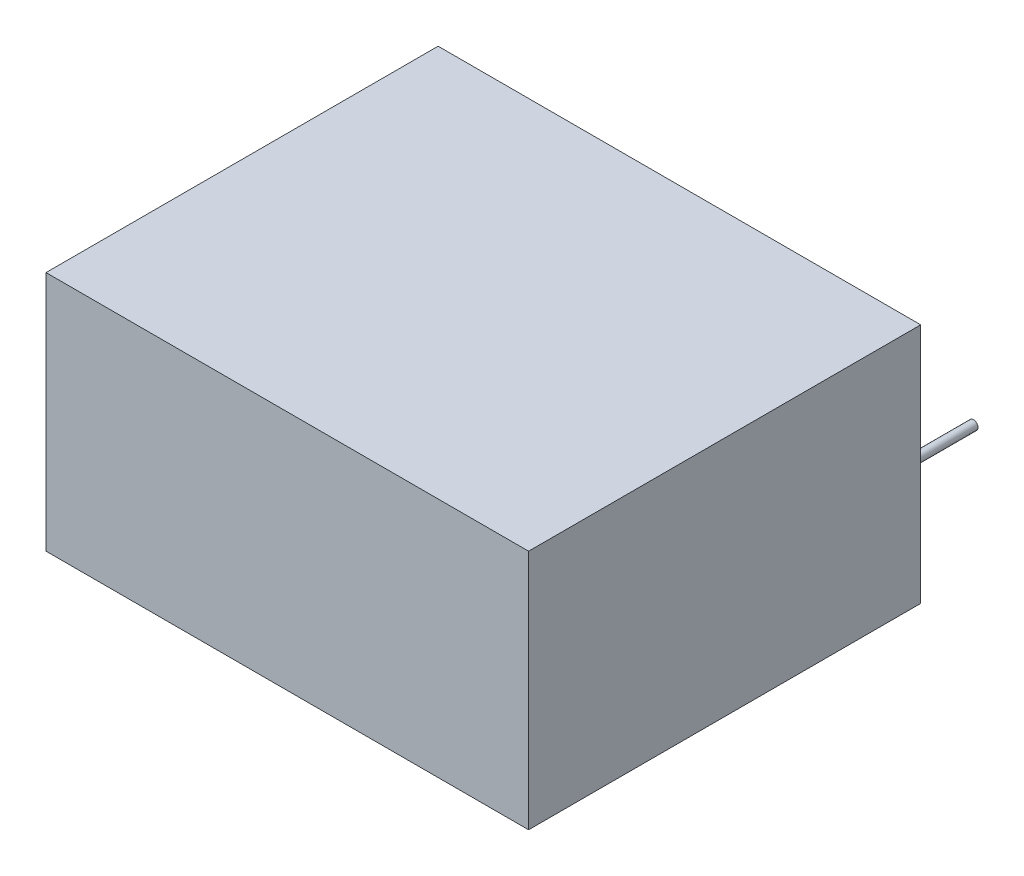
SolidWorks part; units mm, degrees
ref_plane "Front" through (0, 0, 0) normal (0, 0, 1) x (1, 0, 0)
ref_plane "Top" through (0, 0, 0) normal (0, 1, 0) x (1, 0, 0)
ref_plane "Right" through (0, 0, 0) normal (1, 0, 0) x (0, 0, -1)
sketch "Эскиз1" plane through (0, 0, 0) normal (0, 0, 1) x (1, 0, 0)
  line L1 (-0.8, -0.8) -> (0.8, -0.8)
  line L2 (-0.8, -0.8) -> (-0.8, 0.8)
  line L3 (-0.8, 0.8) -> (0.8, 0.8)
  line L4 (0.8, -0.8) -> (0.8, 0.8)
  line L5 (11.65, -0.8) -> (13.25, -0.8)
  line L6 (11.65, -0.8) -> (11.65, 0.8)
  line L7 (11.65, 0.8) -> (13.25, 0.8)
  line L8 (13.25, -0.8) -> (13.25, 0.8)
sketch "Эскиз2" plane through (0, 0, 0) normal (0, 0, 1) x (1, 0, 0)
  line L0 (-0.5, 8) -> (-0.5, -8)
  line L1 (31.5, -8) -> (31.5, 8)
  line L2 (-0.5, -8) -> (31.5, -8)
  line L3 (31.5, 8) -> (-0.5, 8)
  dimension "D1" = 32
  dimension "D2" = 16
  dimension "D3" = 8
  dimension "D4" = 0.5
extrude "Вытянуть1" add sketch "Эскиз2" along normal blind 26
sketch "Эскиз3" plane through (0, 0, 0) normal (0, 0, -1) x (-1, 0, 0)
  circle A0 centre (0, 0) radius 0.4
  circle A1 centre (-31, 0) radius 0.3
  dimension "D1" = 0.8
  dimension "D2" = 31
extrude "Вытянуть2" add sketch "Эскиз3" along normal blind 4
